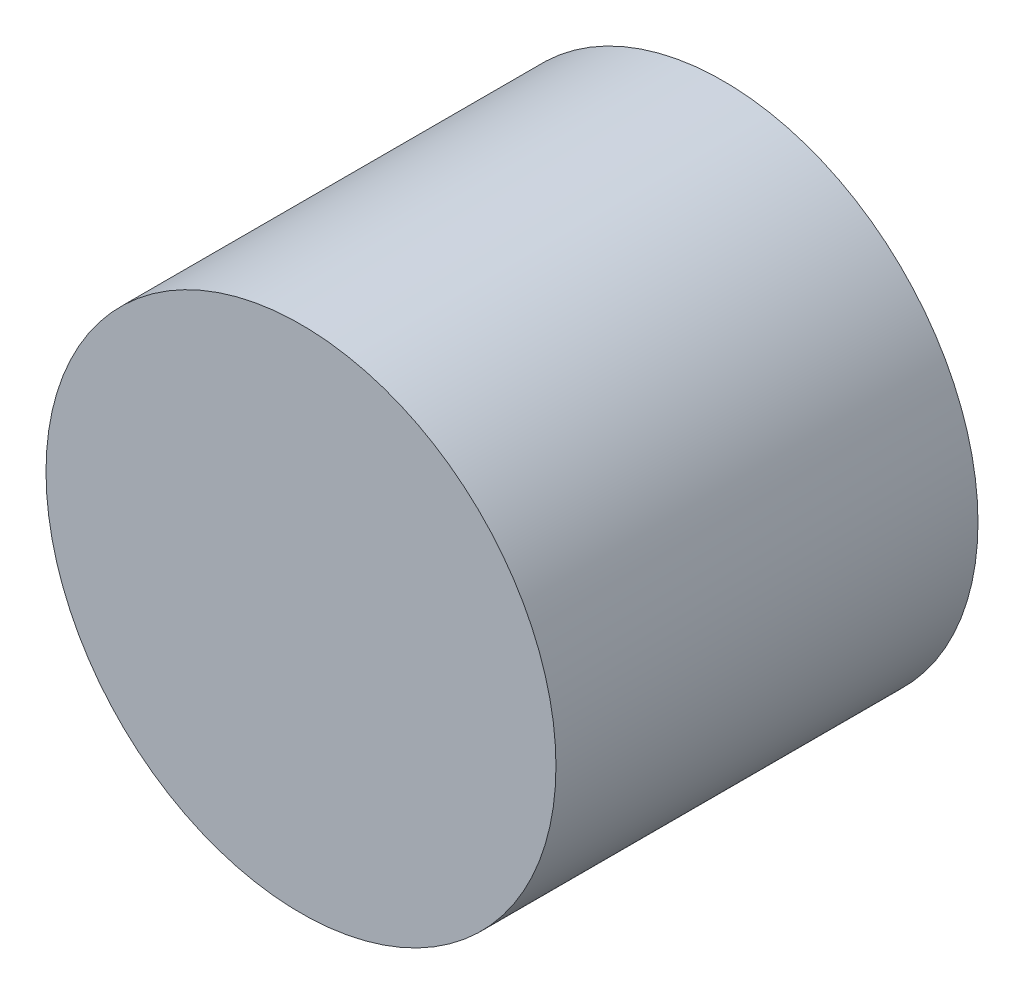
SolidWorks part; units mm, degrees
ref_plane "Piano frontale" through (0, 0, 0) normal (0, 0, 1) x (1, 0, 0)
ref_plane "Piano superiore" through (0, 0, 0) normal (0, 1, 0) x (1, 0, 0)
ref_plane "Piano destro" through (0, 0, 0) normal (1, 0, 0) x (0, 0, -1)
sketch "Schizzo1" plane through (0, 0, 0) normal (0, 0, 1) x (1, 0, 0)
  circle A0 centre (4.1892, -21.3215) radius 14.5 construction
  circle A1 centre (4.1892, -21.3215) radius 14.5
extrude "Estrusione-Estrusione1" add sketch "Schizzo1" along normal up to surface (24 mm away)
sketch "Schizzo2" plane through (0, 0, 0) normal (0, 0, -1) x (-1, 0, 0)
  circle A0 centre (-4.1892, -21.3215) radius 5.1 construction
  circle A1 centre (-4.1892, -21.3215) radius 5.1
extrude "Estrusione-Estrusione2" add sketch "Schizzo2" along normal blind 2
sketch "Schizzo3" plane through (0, 0, -2) normal (0, 0, -1) x (-1, 0, 0)
  arc A0 (-8.0382, -25.422) -> (-6.3296, -26.5223) centre (-4.1892, -21.3215) ccw construction
  arc A1 (-8.0382, -25.422) -> (-6.3296, -26.5223) centre (-4.1892, -21.3215) ccw
  circle A2 centre (-4.1892, -21.3215) radius 5.624
